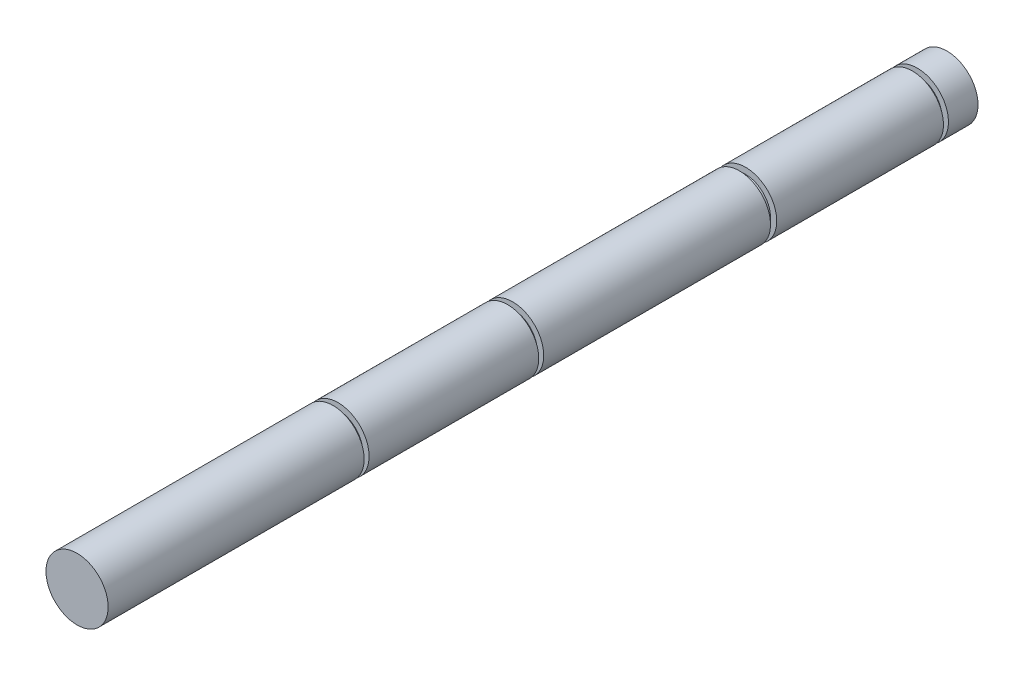
SolidWorks part; units mm, degrees
ref_plane "Front Plane" through (0, 0, 0) normal (0, 0, 1) x (1, 0, 0)
ref_plane "Top Plane" through (0, 0, 0) normal (0, 1, 0) x (1, 0, 0)
ref_plane "Right Plane" through (0, 0, 0) normal (1, 0, 0) x (0, 0, -1)
sketch "Sketch1" plane through (0, 0, 0) normal (0, 0, 1) x (1, 0, 0)
  circle A0 centre (0, 0) radius 5
  dimension "D1" = 10
extrude "Boss-Extrude1" add sketch "Sketch1" along normal blind 135
sketch "Sketch2" plane through (0, 0, 0) normal (0, 1, 0) x (1, 0, 0)
  line L0 (-5, 0) -> (-5, -135) construction
  line L1 (-5, -64.9) -> (-4, -64.9)
  line L2 (-5, -64.9) -> (-5, -65.7)
  line L3 (-5, -65.7) -> (-4, -65.7)
  line L4 (-4, -64.9) -> (-4, -65.7)
  line L5 (-5, -93.8) -> (-4, -93.8)
  line L6 (-5, -93) -> (-5, -93.8)
  line L7 (-5, -93) -> (-4, -93)
  line L8 (-4, -93) -> (-4, -93.8)
  line L9 (0, -6.0506) -> (0, -20.2585) construction
  dimension "D1" = 1
  dimension "D2" = 0.8
  dimension "D3" = 41.2
  dimension "D5" = 27.3
  dimension "D4" = 2
revolve "Cut-Revolve1" cut sketch "Sketch2" angle 360 about L9
sketch "Sketch3" plane through (0, 0, 0) normal (0, 0, -1) x (-1, 0, 0)
  circle A0 centre (0, 0) radius 5 construction
  circle A1 centre (0, 0) radius 5
extrude "Boss-Extrude2" add sketch "Sketch3" along normal blind 5
extrude "Cut-Extrude1" cut sketch "Sketch4" against normal blind 0.8
sketch "Sketch4" plane through (-672.5459, -100.4844, -0.235) normal (0, 0, -1) x (-0.3247, 0.9458, 0)
  circle A0 centre (-123.3622, 668.7278) radius 4
  circle A1 centre (-123.3622, 668.7278) radius 5
extrude "Cut-Extrude2" cut sketch "Sketch5" against normal blind 1
sketch "Sketch5" plane through (-672.5459, -100.4844, 27.4) normal (0, 0, -1) x (-0.3247, 0.9458, 0)
  circle A0 centre (-123.3622, 668.7278) radius 4
  circle A1 centre (-123.3622, 668.7278) radius 5
